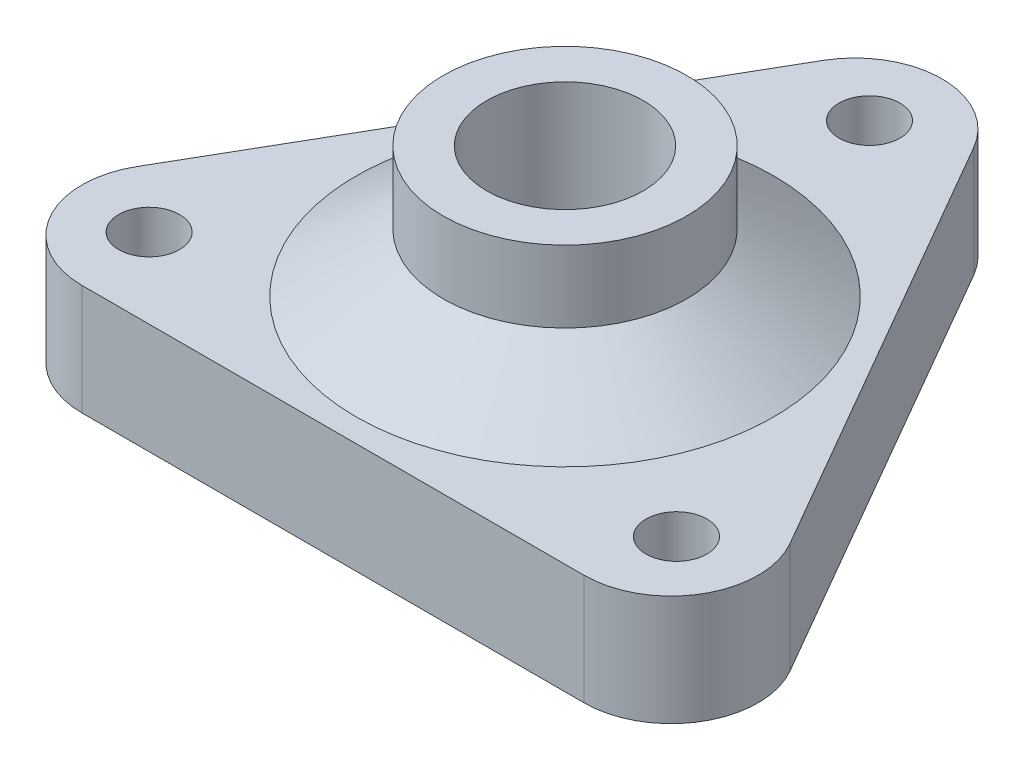
SolidWorks part; units mm, degrees
ref_plane "Front Plane" through (0, 0, 0) normal (0, 0, 1) x (1, 0, 0)
ref_plane "Top Plane" through (0, 0, 0) normal (0, 1, 0) x (1, 0, 0)
ref_plane "Right Plane" through (0, 0, 0) normal (1, 0, 0) x (0, 0, -1)
sketch "Sketch1" plane through (0, 0, 0) normal (0, 1, 0) x (1, 0, 0)
  line L0 (-23.094, -13.3333) -> (23.094, -13.3333)
  line L1 (23.094, -13.3333) -> (0, 26.6667)
  line L2 (0, 26.6667) -> (-23.094, -13.3333)
  line L3 (-23.094, -13.3333) -> (11.547, 6.6667) construction
  line L4 (23.094, -13.3333) -> (-11.547, 6.6667) construction
  line L5 (-15.1554, -8.75) -> (0, 17.5) construction
  line L6 (0, 17.5) -> (15.1554, -8.75) construction
  line L7 (15.1554, -8.75) -> (-15.1554, -8.75) construction
  circle A0 centre (0, 17.5) radius 1.75
  circle A1 centre (-15.1554, -8.75) radius 1.75
  circle A2 centre (15.1554, -8.75) radius 1.75
  circle A3 centre (0, 0) radius 17.5
  circle A4 centre (0, 0) radius 4.5
  point P2 (0, 0)
  dimension "D1" = 35
  dimension "D2" = 3.5
  dimension "D4" = 9
  dimension "D3" = 40
extrude "Boss-Extrude1" add sketch "Sketch1" along normal blind 6.35 contours L0 A3 A2 L1 A0 L2 A1 | A3 L1 L2 A0 | A3 L2 L0 A1 | A3 L0 L1 A2
fillet "Fillet1" radius 5 3 edges at (0, 3.175, -26.6667) (23.094, 3.175, 13.3333) (-23.094, 3.175, 13.3333)
sketch "Sketch2" plane through (0, 6.35, 0) normal (0, 1, 0) x (1, 0, 0)
  circle A0 centre (0, 0) radius 7
  circle A1 centre (0, 0) radius 4.5
  circle A2 centre (0, 0) radius 4.5 construction
  dimension "D1" = 14
extrude "Boss-Extrude2" add sketch "Sketch2" along normal blind 7.5
chamfer "Chamfer1" distance 5 angle 34 1 edges at (0, 6.35, 7)
